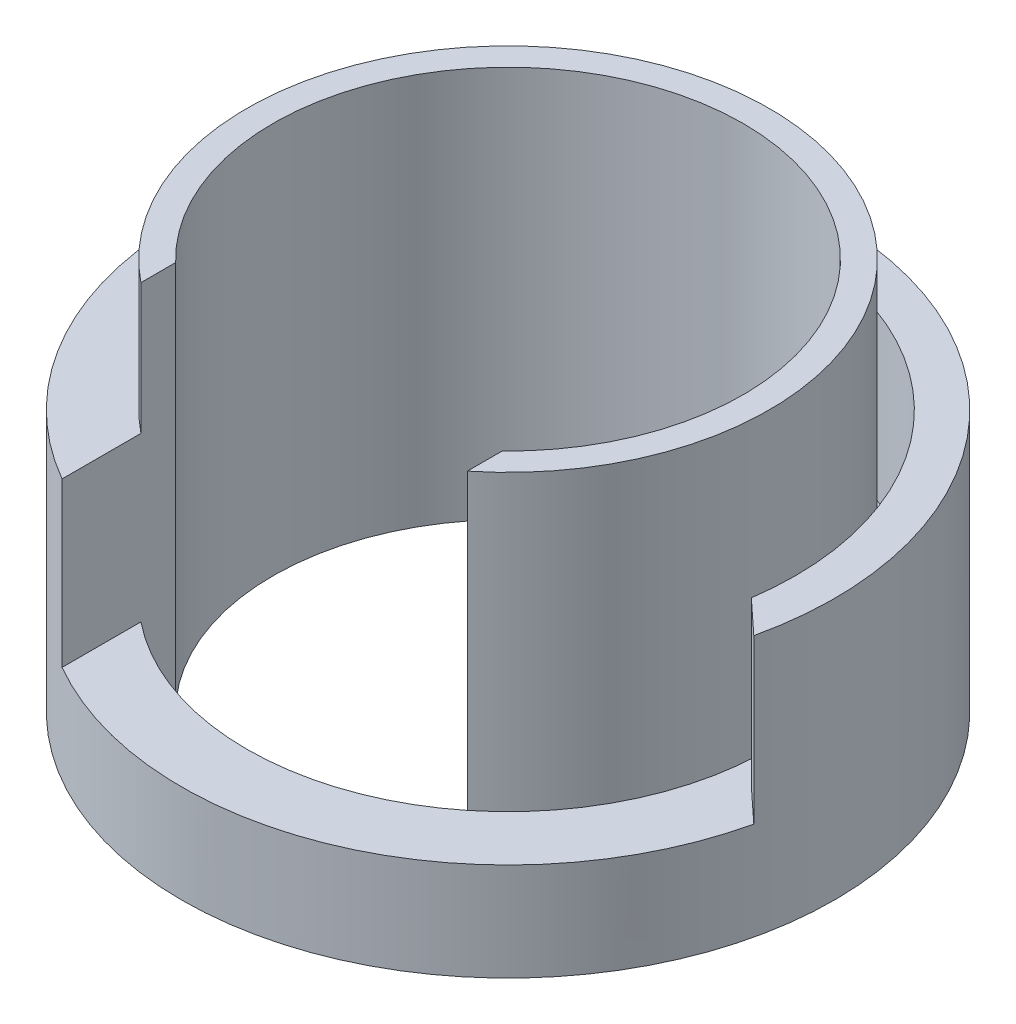
SolidWorks part; units mm, degrees
ref_plane "Plano frontal" through (0, 0, 0) normal (0, 0, 1) x (1, 0, 0)
ref_plane "Plano superior" through (0, 0, 0) normal (0, 1, 0) x (1, 0, 0)
ref_plane "Plano direito" through (0, 0, 0) normal (1, 0, 0) x (0, 0, -1)
sketch "Esboço1" plane through (0, 0, 0) normal (0, 1, 0) x (1, 0, 0)
  line L0 (0, 0) -> (-10, 0) construction
  line L1 (0, 0) -> (10, 0) construction
  line L2 (-10, 0) -> (-10, -17.3205) construction
  line L3 (10, 0) -> (10, -17.3205) construction
  line L4 (10, -27.2235) -> (-10, -27.2235) construction
  line L9 (-10, -22.9129) -> (-10, -27.2235) construction
  line L11 (10, -22.9129) -> (10, -27.2235) construction
  arc A1 (12.5, -21.6506) -> (-12.5, -21.6506) centre (0, 0) ccw
  circle A2 centre (0, 0) radius 20
  circle A3 centre (0, 0) radius 25
extrude "Ressalto-extrusão2" add sketch "Esboço1" along normal blind 20 contours A1 A3 A2
sketch "Esboço2" plane through (0, 20, 0) normal (0, 1, 0) x (1, 0, 0)
  line L4 (-12.5, -15.6125) -> (-12.5, -12.9518)
  line L5 (12.5, -15.6125) -> (12.5, -12.9518)
  arc A0 (12.5, -15.6125) -> (-12.5, -15.6125) centre (0, 0) ccw
  arc A1 (12.5, -12.9518) -> (-12.5, -12.9518) centre (0, 0) ccw
  dimension "D1" = 36
  dimension "D2" = 20
extrude "Ressalto-extrusão3" add sketch "Esboço2" along normal blind 10 and the other way up to surface other way up to face at (0, 0, 20)
ref_plane "Plano1" through (0, 20, 0) normal (0, 1, 0) x (1, 0, 0)
sketch "Esboço4" plane through (0, 20, 0) normal (0, 1, 0) x (1, 0, 0)
  line L0 (-10.5202, 9.7567) -> (-20.9474, 19.4271)
  line L4 (16.2215, 2.004) -> (30.3575, -11.1061)
  line L6 (-0.6455, 1.7303) -> (-0.2136, 0.5726)
  line L7 (-14.0895, 37.7688) -> (-7.6894, 20.6125) construction
sketch "Esboço3" plane through (0, 20, 0) normal (0, 1, 0) x (1, 0, 0)
  line L0 (-18.3303, 17) -> (-14.6642, 13.6)
  line L2 (3.0981, 24.8073) -> (2.7263, 21.8304)
  line L3 (-12.5, -21.6506) -> (-12.5, -15.6125)
  line L4 (21.774, -3.1455) -> (24.3745, -5.5573)
  line L7 (-10.5202, 9.7567) -> (-20.9474, 19.4271) construction
  line L8 (-12.5, -15.6125) -> (-12.5, -12.9518) construction
  arc A1 (3.0981, 24.8073) -> (-18.3303, 17) centre (0, 0) ccw
  arc A2 (-12.5, -15.6125) -> (-14.6642, 13.6) centre (0, 0) ccw
  arc A3 (21.774, -3.1455) -> (2.7263, 21.8304) centre (0, 0) ccw
  arc A4 (-12.5, -21.6506) -> (24.3745, -5.5573) centre (0, 0) ccw
  arc A5 (-12.5, -15.6125) -> (12.5, -15.6125) centre (0, 0) ccw construction
  arc A6 (12.5, -15.6125) -> (-12.5, -15.6125) centre (0, 0) ccw construction
  circle A7 centre (0, 0) radius 25 construction
extrude "Corte-extrusão2" cut sketch "Esboço3" against normal blind 12.5
